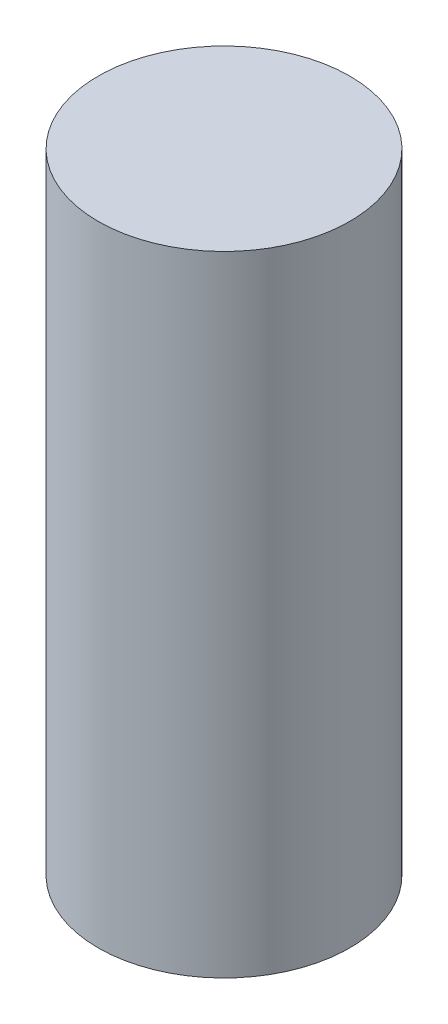
SolidWorks part; units mm, degrees
ref_plane "Front Plane" through (0, 0, 0) normal (0, 0, 1) x (1, 0, 0)
ref_plane "Top Plane" through (0, 0, 0) normal (0, 1, 0) x (1, 0, 0)
ref_plane "Right Plane" through (0, 0, 0) normal (1, 0, 0) x (0, 0, -1)
sketch "Sketch1" plane through (0, 0, 0) normal (0, 1, 0) x (1, 0, 0)
  circle A0 centre (0, 0) radius 8
  dimension "D1" = 16
extrude "Boss-Extrude1" add sketch "Sketch1" against normal blind 40
